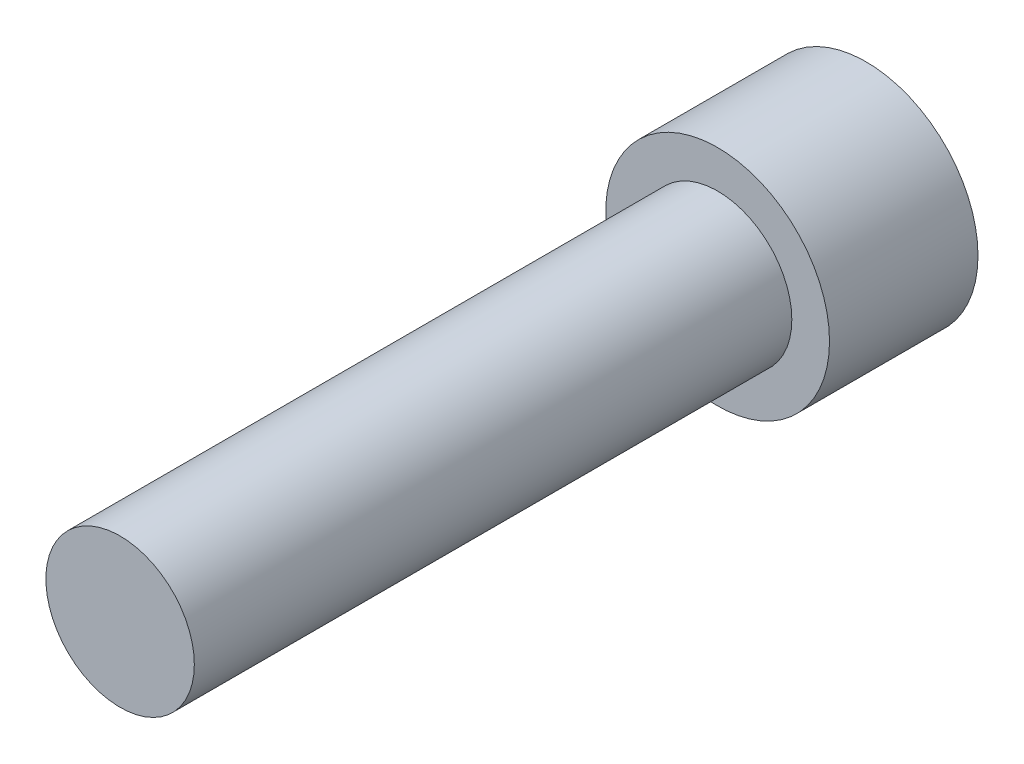
SolidWorks part; units mm, degrees
ref_plane "Front Plane" through (0, 0, 0) normal (0, 0, 1) x (1, 0, 0)
ref_plane "Top Plane" through (0, 0, 0) normal (0, 1, 0) x (1, 0, 0)
ref_plane "Right Plane" through (0, 0, 0) normal (1, 0, 0) x (0, 0, -1)
sketch "Sketch1" plane through (0, 0, 0) normal (0, 0, 1) x (1, 0, 0)
  circle A0 centre (0, 0) radius 5.955
extrude "Head" add sketch "Sketch1" along normal blind 7.9
ref_plane "Plane_z7_9" through (0, 0, 7.9) normal (0, 0, 1) x (1, 0, 0)
sketch "Sketch2" plane through (0, 0, 7.9) normal (0, 0, 1) x (1, 0, 0)
  circle A0 centre (0, 0) radius 3.95
extrude "Shank" add sketch "Sketch2" along normal blind 31.79
